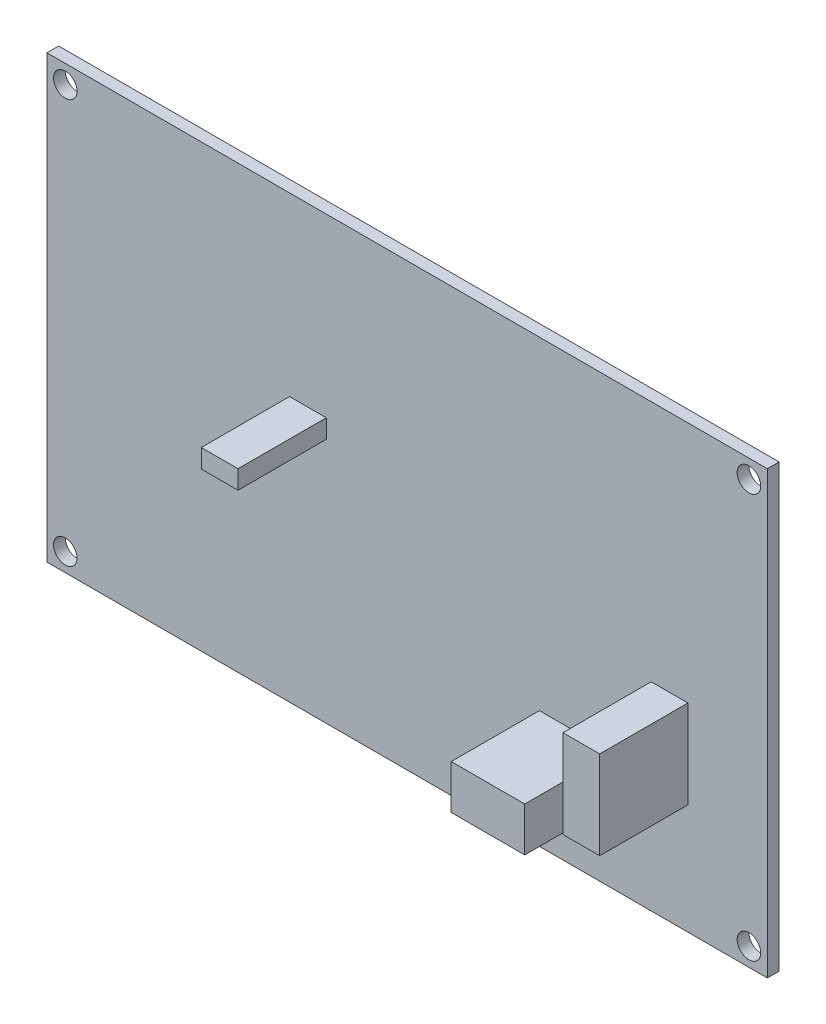
SolidWorks part; units mm, degrees
ref_plane "Plan de face" through (0, 0, 0) normal (0, 0, 1) x (1, 0, 0)
ref_plane "Plan de dessus" through (0, 0, 0) normal (0, 1, 0) x (1, 0, 0)
ref_plane "Plan de droite" through (0, 0, 0) normal (1, 0, 0) x (0, 0, -1)
sketch "Esquisse1" plane through (0, 0, 0) normal (0, 0, 1) x (1, 0, 0)
  line L1 (-49, 30) -> (49, 30)
  line L2 (-49, 30) -> (-49, -30)
  line L3 (-49, -30) -> (49, -30)
  line L4 (49, 30) -> (49, -30)
  line L5 (-49, 30) -> (49, -30) construction
  line L6 (-49, -30) -> (49, 30) construction
  point P0 (0, 0)
  dimension "D1" = 60
  dimension "D2" = 98
extrude "Boss.-Extru.1" add sketch "Esquisse1" along normal blind 1.6
sketch "Esquisse2" plane through (0, 0, 1.6) normal (0, 0, 1) x (1, 0, 0)
  line L0 (49, 30) -> (-49, 30) construction
  line L1 (-49, 30) -> (-49, -30) construction
  circle A0 centre (-46.5, 27.5) radius 1.6
  dimension "D1" = 3.2
  dimension "D2" = 2.5
  dimension "D3" = 2.5
extrude "Enlèv. mat.-Extru.1" cut sketch "Esquisse2" against normal through all
mirror "Symétrie1" about plane through (0, 0, 0) normal (0, 1, 0) of "Enlèv. mat.-Extru.1"
mirror "Symétrie2" about plane through (0, 0, 0) normal (1, 0, 0) of "Symétrie1", "Enlèv. mat.-Extru.1"
sketch "Esquisse3" plane through (0, 0, 1.6) normal (0, 0, 1) x (1, 0, 0)
  line L0 (49, 30) -> (-49, 30) construction
  line L1 (33.2, -3) -> (38.2, -3)
  line L2 (33.2, -3) -> (33.2, -15)
  line L3 (33.2, -15) -> (38.2, -15)
  line L4 (38.2, -3) -> (38.2, -15)
  line L5 (49, -30) -> (49, 30) construction
  line L6 (-49, -30) -> (49, -30) construction
  line L7 (18, -14) -> (28, -14)
  line L8 (18, -14) -> (18, -20)
  line L9 (18, -20) -> (28, -20)
  line L10 (28, -14) -> (28, -20)
  line L12 (-16, 6) -> (-11, 6)
  line L13 (-16, 6) -> (-16, 3.46)
  line L14 (-16, 3.46) -> (-11, 3.46)
  line L15 (-11, 6) -> (-11, 3.46)
  dimension "D1" = 12
  dimension "D2" = 5
  dimension "D3" = 33
  dimension "D4" = 10.8
  dimension "D5" = 6
  dimension "D6" = 10
  dimension "D7" = 21
  dimension "D8" = 10
  dimension "D9" = 2.54
  dimension "D10" = 5
  dimension "D11" = 24
  dimension "D12" = 60
extrude "Boss.-Extru.2" add sketch "Esquisse3" along normal blind 12
